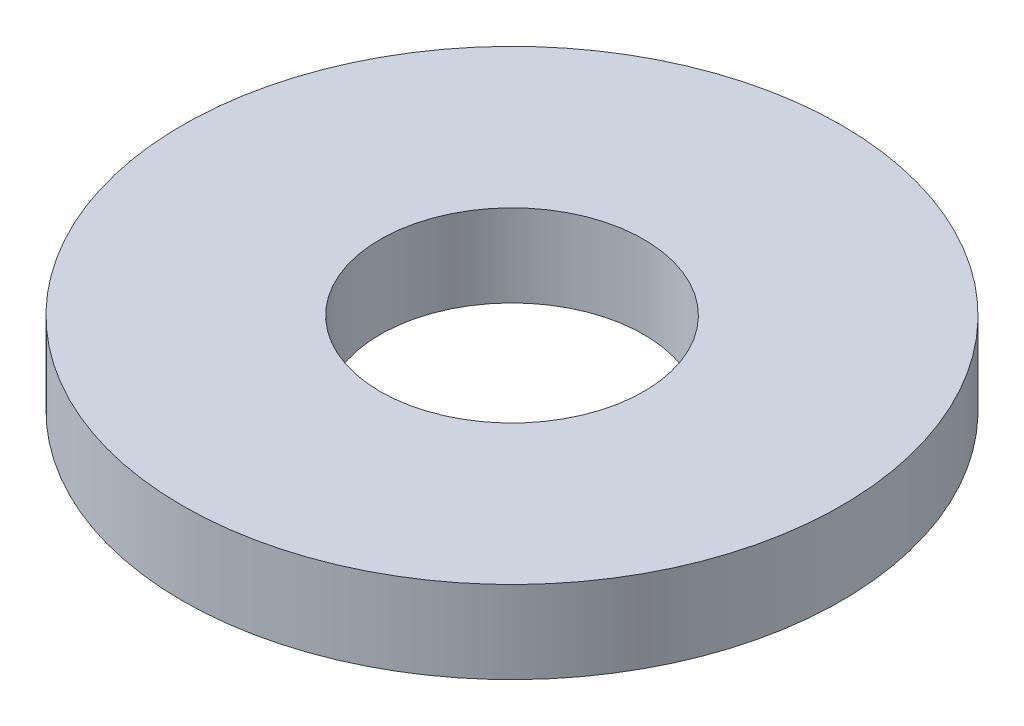
SolidWorks part; units mm, degrees
ref_plane "Front Plane" through (0, 0, 0) normal (0, 0, 1) x (1, 0, 0)
ref_plane "Top Plane" through (0, 0, 0) normal (0, 1, 0) x (1, 0, 0)
ref_plane "Right Plane" through (0, 0, 0) normal (1, 0, 0) x (0, 0, -1)
sketch "Sketch1" plane through (0, 0, 0) normal (0, 1, 0) x (1, 0, 0)
  circle A0 centre (0, 0) radius 2.54
  circle A1 centre (0, 0) radius 6.35
  dimension "D1" = 5.08
  dimension "D2" = 12.7
extrude "Boss-Extrude1" add sketch "Sketch1" along normal blind 1.5875
